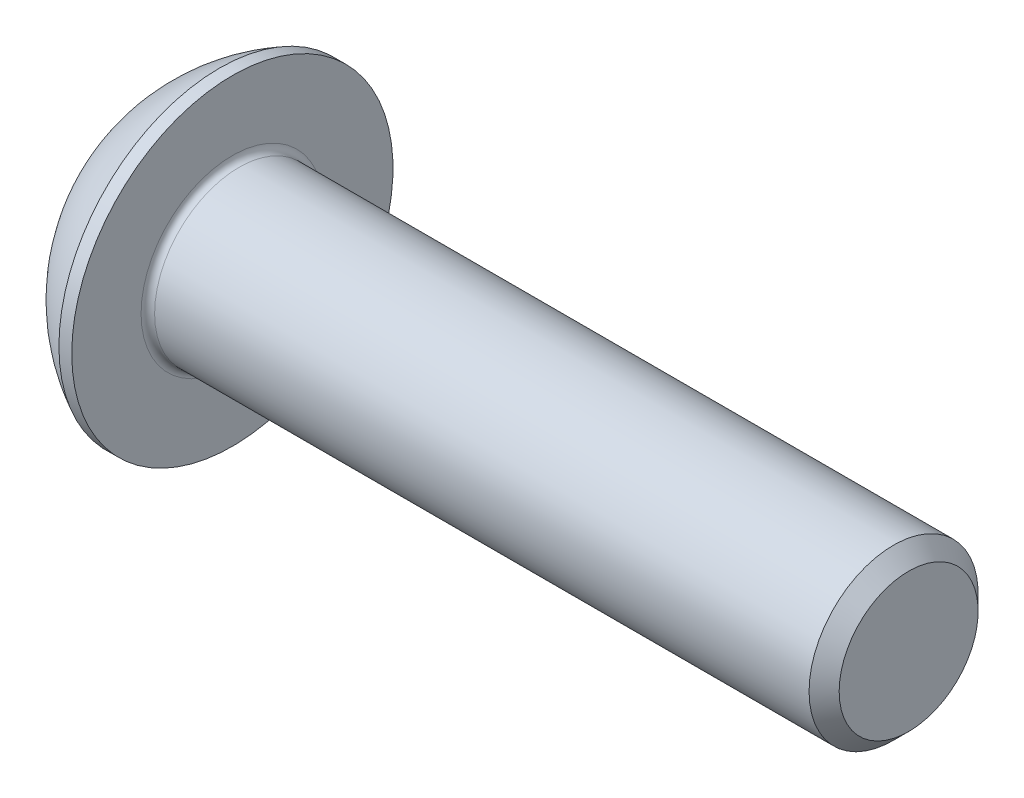
SolidWorks part; units mm, degrees
material "AISI 4340 Steel, annealed"
ref_plane "Plane1" through (0, 0, 0) normal (0, 0, 1) x (1, 0, 0)
ref_plane "Plane2" through (0, 0, 0) normal (0, 1, 0) x (1, 0, 0)
ref_plane "Plane3" through (0, 0, 0) normal (1, 0, 0) x (0, 0, -1)
other "Configuration Table"
sketch "BodySke" plane through (0, 0, 0) normal (0, 0, 1) x (1, 0, 0)
  line L0 (22.75, 0) -> (22.75, 2.055)
  line L1 (22.305, 2.5) -> (2.75, 2.5)
  line L2 (2.75, 2.5) -> (2.75, 4.75)
  line L3 (2.75, 4.75) -> (2.37, 4.75)
  line L4 (0, 0) -> (101.6, 0) construction
  line L5 (2.75, -4.75) -> (2.37, -4.75) construction
  line L6 (55.6768, -2.5) -> (2.75, -2.5) construction
  line L7 (22.75, 0) -> (0, 0)
  line L8 (0, 2.375) -> (0, -2.375) construction
  line L9 (0, 0) -> (0, 2.375)
  line L10 (22.75, 2.055) -> (22.305, 2.5)
  line L11 (22.75, -2.055) -> (22.305, -2.5) construction
  line L12 (3.55, 9.525) -> (3.55, -2.5) construction
  line L13 (2.75, 9.525) -> (2.75, -2.5) construction
  arc A1 (0, 2.375) -> (2.37, 4.75) centre (4.755, 0) cw
  dimension "Head_side_ht" = 0.38
  dimension "Body_ch_ang" = 45
revolve "BaseBody" add sketch "BodySke" angle 360 about L4
cosmetic thread "ThreadCosmetic" [suppressed] parameters "Thread_length"=18.4, "Thread_minor"=4.11
fillet "Fillet1" radius 0.2 1 edges at (2.75, 0, 2.5)
sketch "Sketch2" plane through (0, 0, 0) normal (0, 0, 1) x (1, 0, 0)
  line L0 (0, 1.5) -> (1.56, 1.5)
  line L1 (1.56, 1.5) -> (2.426, 0)
  line L3 (2.426, 0) -> (0, 0)
  line L4 (0, 0) -> (0, 1.5)
  line L5 (0, -1.5) -> (1.56, -1.5) construction
  line L6 (0, 0) -> (47.625, 0) construction
  dimension "D2" = 60
  dimension "PreBroach_depth" = 1.56
  dimension "PreBroach_dia" = 3
revolve "PreBroach" cut sketch "Sketch2" angle 360 about L6
sketch "Sketch3" plane through (0, 0, 0) normal (1, 0, 0) x (0, 0, -1)
  line L0 (-1.5, -0.866) -> (-1.5, 0.866)
  line L1 (-1.5, 0.866) -> (0, 1.7321)
  line L2 (0, 1.7321) -> (1.5, 0.866)
  line L3 (1.5, 0.866) -> (1.5, -0.866)
  line L4 (1.5, -0.866) -> (0, -1.7321)
  line L5 (0, -1.7321) -> (-1.5, -0.866)
extrude "Hex" cut sketch "Sketch3" along normal blind 1.56
sketch "ThdSchSke" plane through (0, 0, 0) normal (0, 0, 1) x (1, 0, 0)
  line L0 (4.35, -2.055) -> (4.0384, -2.5)
  line L1 (4.35, -2.055) -> (4.6616, -2.5)
  line L2 (4.6616, -2.5) -> (4.6616, -3.125)
  line L3 (-3.175, 0) -> (5.1513, 0) construction
  line L5 (4.6616, -3.125) -> (4.0384, -3.125)
  line L6 (4.0384, -3.125) -> (4.0384, -2.5)
  dimension "SideAngle" = 55
  dimension "VeeAngle" = 70
revolve "ThreadSchematic" [suppressed] cut sketch "ThdSchSke" angle 360 about L3
pattern_linear "ThdSchPat" [suppressed]
equation "\"D1@BodySke\" = \"Head_dia@BodySke\" * .5"
equation "\"Thread_minor@ThreadCosmetic\" = \"Minor_dia@BodySke\""
equation "\"D1@Sketch3\" = \"Hex_size@Sketch3\" / 2"
equation "\"D2@Sketch3\" = \"D1@Sketch3\""
equation "\"D3@Sketch3\" = \"Hex_size@Sketch3\""
equation "\"Thread_length@ThreadCosmetic\" = ((sgn( (\"Length@BodySke\" - \"Advance@BodySke\" * 2.0) - \"Thread_nom@BodySke\" )-1)*( (\"Length@BodySke\" - \"Advance@BodySke\" * 2.0) - \"Thread_nom@BodySke\" ))/-2+ \"Thread_nom@BodySke\""
equation "\"Thread_minor@ThdSchSke\" = \"Minor_dia@BodySke\""
equation "\"Diameter@ThdSchSke\" = \"Diameter@BodySke\""
equation "\"Overcut@ThdSchSke\" = \"Diameter@BodySke\" * 1.25"
equation "\"Start@ThdSchSke\" = \"Head_ht@BodySke\" + \"Length@BodySke\" - \"Thread_length@ThreadCosmetic\"  '---Non-countersunk---"
equation "\"Num_threads@ThdSchPat\" = int( \"Thread_length@ThreadCosmetic\" / \"Advance@BodySke\" + 0.999 )  + 1"
equation "\"Advance@ThdSchPat\" = \"Thread_length@ThreadCosmetic\" /  (\"Num_threads@ThdSchPat\" - 1) 'relax it"
equation "\"Num_threads@ThdSchPat\" = \"Num_threads@ThdSchPat\" - sgn( \"Num_threads@ThdSchPat\" - 1) '---chamfered tips only---"
